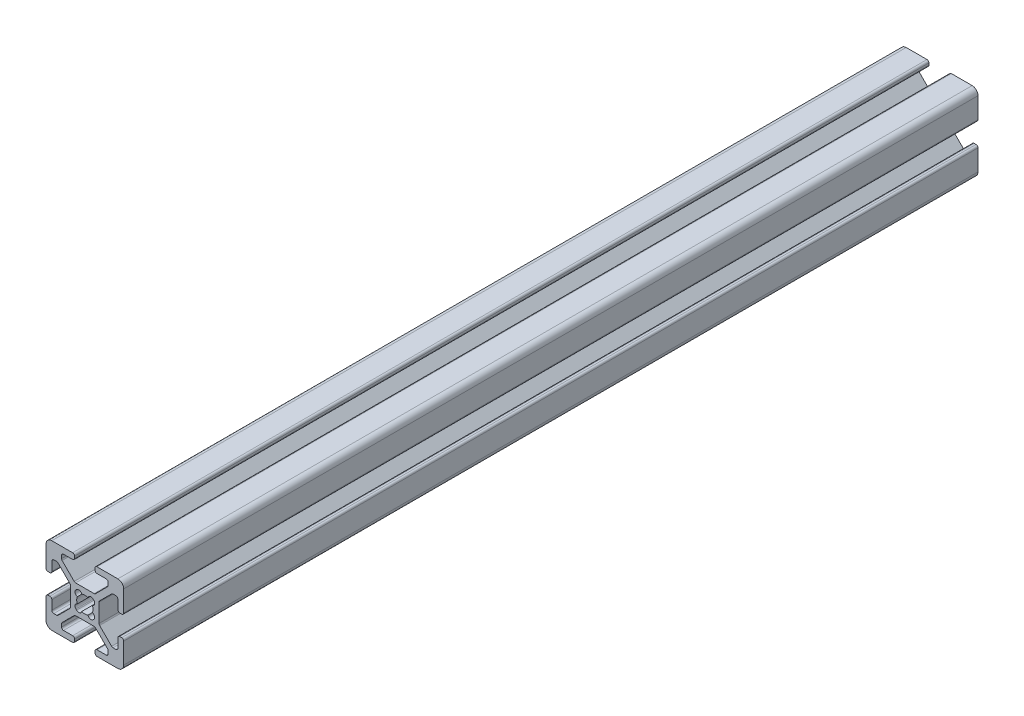
SolidWorks part; units mm, degrees
ref_plane "Front Plane" through (0, 0, 0) normal (0, 0, 1) x (1, 0, 0)
ref_plane "Top Plane" through (0, 0, 0) normal (0, 1, 0) x (1, 0, 0)
ref_plane "Right Plane" through (0, 0, 0) normal (1, 0, 0) x (0, 0, -1)
sketch "Sketch1" plane through (0, 0, 0) normal (0, 0, 1) x (1, 0, 0)
  line L0 (-5.0323, -0.3411) -> (-5.5163, -0.3411)
  line L1 (-6.0243, 0.1669) -> (-6.0243, 2.5159)
  line L2 (-4.5243, 0.1669) -> (-4.5243, 5.5289)
  line L3 (-10.8693, -5.355) -> (-10.8693, -0.5871)
  line L4 (-7.2582, 3.0239) -> (-6.5323, 3.0239)
  line L5 (-7.6174, 2.8752) -> (-10.7205, -0.2279)
  line L6 (-5.0323, -5.6011) -> (-5.5163, -5.6011)
  line L7 (-4.5243, -6.1091) -> (-4.5243, -11.4711)
  line L8 (-6.0243, -6.1091) -> (-6.0243, -8.4581)
  line L9 (-7.2582, -8.9661) -> (-6.5323, -8.9661)
  line L10 (-7.6174, -8.8173) -> (-10.7205, -5.7142)
  line L11 (-12.3994, -5.2756) -> (-12.2198, -5.096)
  line L12 (-17.1543, 6.5209) -> (-17.1543, 6.0369)
  line L13 (-17.6623, 7.0289) -> (-23.0243, 7.0289)
  line L14 (-17.6623, 5.5289) -> (-20.0113, 5.5289)
  line L15 (-12.1404, 0.6839) -> (-16.9082, 0.6839)
  line L16 (-20.5193, 4.295) -> (-20.5193, 5.0209)
  line L17 (-20.3705, 3.9358) -> (-17.2674, 0.8327)
  line L18 (-11.8943, 6.5209) -> (-11.8943, 6.0369)
  line L19 (-11.3863, 7.0289) -> (-6.0243, 7.0289)
  line L20 (-11.3863, 5.5289) -> (-9.0373, 5.5289)
  line L21 (-8.5293, 4.295) -> (-8.5293, 5.0209)
  line L22 (-8.6781, 3.9358) -> (-11.7812, 0.8327)
  line L23 (-12.2198, -0.8462) -> (-12.3994, -0.6666)
  line L24 (-24.0163, -5.6011) -> (-23.5323, -5.6011)
  line L25 (-24.5243, -6.1091) -> (-24.5243, -11.4711)
  line L26 (-23.0243, -6.1091) -> (-23.0243, -8.4581)
  line L27 (-18.1793, -0.5871) -> (-18.1793, -5.355)
  line L28 (-21.7904, -8.9661) -> (-22.5163, -8.9661)
  line L29 (-21.4312, -8.8173) -> (-18.3281, -5.7142)
  line L30 (-24.0163, -0.3411) -> (-23.5323, -0.3411)
  line L31 (-24.5243, 0.1669) -> (-24.5243, 5.5289)
  line L32 (-23.0243, 0.1669) -> (-23.0243, 2.5159)
  line L33 (-21.7904, 3.0239) -> (-22.5163, 3.0239)
  line L34 (-21.4312, 2.8752) -> (-18.3281, -0.2279)
  line L35 (-16.6492, -0.6666) -> (-16.8288, -0.8462)
  line L36 (-11.8943, -12.4631) -> (-11.8943, -11.9791)
  line L37 (-11.3863, -12.9711) -> (-6.0243, -12.9711)
  line L38 (-11.3863, -11.4711) -> (-9.0373, -11.4711)
  line L39 (-16.9082, -6.6261) -> (-12.1404, -6.6261)
  line L40 (-8.5293, -10.2371) -> (-8.5293, -10.9631)
  line L41 (-8.6781, -9.8779) -> (-11.7812, -6.7748)
  line L42 (-17.1543, -12.4631) -> (-17.1543, -11.9791)
  line L43 (-17.6623, -12.9711) -> (-23.0243, -12.9711)
  line L44 (-17.6623, -11.4711) -> (-20.0113, -11.4711)
  line L45 (-20.5193, -10.2371) -> (-20.5193, -10.9631)
  line L46 (-20.3705, -9.8779) -> (-17.2674, -6.7748)
  line L47 (-16.8288, -5.096) -> (-16.6492, -5.2756)
  arc A0 (-15.3283, -4.9062) -> (-13.7203, -4.9062) centre (-14.5243, -2.9711) ccw
  arc A1 (-6.0243, 2.5159) -> (-6.5323, 3.0239) centre (-6.5323, 2.5159) ccw
  arc A2 (-7.2582, 3.0239) -> (-7.6174, 2.8752) centre (-7.2582, 2.5159) ccw
  arc A3 (-10.7205, -0.2279) -> (-10.8693, -0.5871) centre (-10.3613, -0.5871) ccw
  arc A4 (-10.8693, -5.355) -> (-10.7205, -5.7142) centre (-10.3613, -5.355) ccw
  arc A5 (-7.6174, -8.8173) -> (-7.2582, -8.9661) centre (-7.2582, -8.4581) ccw
  arc A6 (-6.5323, -8.9661) -> (-6.0243, -8.4581) centre (-6.5323, -8.4581) ccw
  arc A7 (-5.5163, -5.6011) -> (-6.0243, -6.1091) centre (-5.5163, -6.1091) ccw
  arc A8 (-4.5243, -6.1091) -> (-5.0323, -5.6011) centre (-5.0323, -6.1091) ccw
  arc A9 (-5.0323, -0.3411) -> (-4.5243, 0.1669) centre (-5.0323, 0.1669) ccw
  arc A10 (-6.0243, 0.1669) -> (-5.5163, -0.3411) centre (-5.5163, 0.1669) ccw
  arc A11 (-13.7203, -4.9062) -> (-12.3994, -5.2756) centre (-12.9559, -4.7191) ccw
  arc A12 (-12.2198, -5.096) -> (-12.5892, -3.775) centre (-12.7763, -4.5395) ccw
  arc A13 (-17.1543, 6.5209) -> (-17.6623, 7.0289) centre (-17.6623, 6.5209) ccw
  arc A14 (-17.6623, 5.5289) -> (-17.1543, 6.0369) centre (-17.6623, 6.0369) ccw
  arc A15 (-12.5892, -3.775) -> (-12.5892, -2.1671) centre (-14.5243, -2.9711) ccw
  arc A16 (-17.2674, 0.8327) -> (-16.9082, 0.6839) centre (-16.9082, 1.1919) ccw
  arc A17 (-20.0113, 5.5289) -> (-20.5193, 5.0209) centre (-20.0113, 5.0209) ccw
  arc A18 (-20.5193, 4.295) -> (-20.3705, 3.9358) centre (-20.0113, 4.295) ccw
  arc A19 (-11.8943, 6.0369) -> (-11.3863, 5.5289) centre (-11.3863, 6.0369) ccw
  arc A20 (-11.3863, 7.0289) -> (-11.8943, 6.5209) centre (-11.3863, 6.5209) ccw
  arc A21 (-8.5293, 5.0209) -> (-9.0373, 5.5289) centre (-9.0373, 5.0209) ccw
  arc A22 (-8.6781, 3.9358) -> (-8.5293, 4.295) centre (-9.0373, 4.295) ccw
  arc A23 (-12.1404, 0.6839) -> (-11.7812, 0.8327) centre (-12.1404, 1.1919) ccw
  arc A24 (-12.5892, -2.1671) -> (-12.2198, -0.8462) centre (-12.7763, -1.4027) ccw
  arc A25 (-12.3994, -0.6666) -> (-13.7203, -1.0359) centre (-12.9559, -1.223) ccw
  arc A26 (-24.0163, -5.6011) -> (-24.5243, -6.1091) centre (-24.0163, -6.1091) ccw
  arc A27 (-23.0243, -6.1091) -> (-23.5323, -5.6011) centre (-23.5323, -6.1091) ccw
  arc A28 (-13.7203, -1.0359) -> (-15.3283, -1.0359) centre (-14.5243, -2.9711) ccw
  arc A29 (-18.3281, -5.7142) -> (-18.1793, -5.355) centre (-18.6873, -5.355) ccw
  arc A30 (-23.0243, -8.4581) -> (-22.5163, -8.9661) centre (-22.5163, -8.4581) ccw
  arc A31 (-21.7904, -8.9661) -> (-21.4312, -8.8173) centre (-21.7904, -8.4581) ccw
  arc A32 (-23.5323, -0.3411) -> (-23.0243, 0.1669) centre (-23.5323, 0.1669) ccw
  arc A33 (-24.5243, 0.1669) -> (-24.0163, -0.3411) centre (-24.0163, 0.1669) ccw
  arc A34 (-22.5163, 3.0239) -> (-23.0243, 2.5159) centre (-22.5163, 2.5159) ccw
  arc A35 (-21.4312, 2.8752) -> (-21.7904, 3.0239) centre (-21.7904, 2.5159) ccw
  arc A36 (-18.1793, -0.5871) -> (-18.3281, -0.2279) centre (-18.6873, -0.5871) ccw
  arc A37 (-15.3283, -1.0359) -> (-16.6492, -0.6666) centre (-16.0927, -1.223) ccw
  arc A38 (-16.8288, -0.8462) -> (-16.4594, -2.1671) centre (-16.2723, -1.4027) ccw
  arc A39 (-11.8943, -12.4631) -> (-11.3863, -12.9711) centre (-11.3863, -12.4631) ccw
  arc A40 (-11.3863, -11.4711) -> (-11.8943, -11.9791) centre (-11.3863, -11.9791) ccw
  arc A41 (-16.4594, -2.1671) -> (-16.4594, -3.775) centre (-14.5243, -2.9711) ccw
  arc A42 (-11.7812, -6.7748) -> (-12.1404, -6.6261) centre (-12.1404, -7.1341) ccw
  arc A43 (-9.0373, -11.4711) -> (-8.5293, -10.9631) centre (-9.0373, -10.9631) ccw
  arc A44 (-8.5293, -10.2371) -> (-8.6781, -9.8779) centre (-9.0373, -10.2371) ccw
  arc A45 (-17.1543, -11.9791) -> (-17.6623, -11.4711) centre (-17.6623, -11.9791) ccw
  arc A46 (-17.6623, -12.9711) -> (-17.1543, -12.4631) centre (-17.6623, -12.4631) ccw
  arc A47 (-20.5193, -10.9631) -> (-20.0113, -11.4711) centre (-20.0113, -10.9631) ccw
  arc A48 (-20.3705, -9.8779) -> (-20.5193, -10.2371) centre (-20.0113, -10.2371) ccw
  arc A49 (-16.9082, -6.6261) -> (-17.2674, -6.7748) centre (-16.9082, -7.1341) ccw
  arc A50 (-16.4594, -3.775) -> (-16.8288, -5.096) centre (-16.2723, -4.5395) ccw
  arc A51 (-16.6492, -5.2756) -> (-15.3283, -4.9062) centre (-16.0927, -4.7191) ccw
  arc A52 (-4.5243, 5.5289) -> (-6.0243, 7.0289) centre (-6.0243, 5.5289) ccw
  arc A53 (-6.0243, -12.9711) -> (-4.5243, -11.4711) centre (-6.0243, -11.4711) ccw
  arc A54 (-24.5243, -11.4711) -> (-23.0243, -12.9711) centre (-23.0243, -11.4711) ccw
  arc A55 (-23.0243, 7.0289) -> (-24.5243, 5.5289) centre (-23.0243, 5.5289) ccw
extrude "Extrude1" add sketch "Sketch1" along normal blind 220
